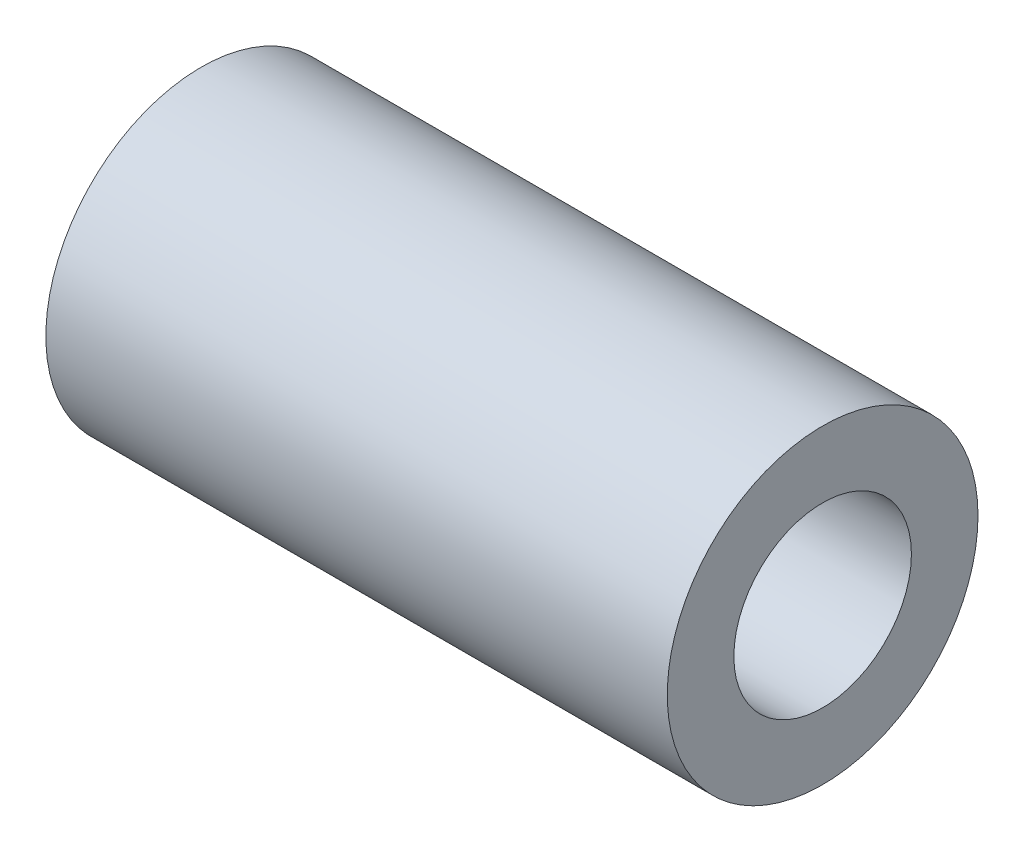
SolidWorks part; units mm, degrees
material "Brass"
ref_plane "Front Plane" through (0, 0, 0) normal (0, 0, 1) x (1, 0, 0)
ref_plane "Top Plane" through (0, 0, 0) normal (0, 1, 0) x (1, 0, 0)
ref_plane "Right Plane" through (0, 0, 0) normal (1, 0, 0) x (0, 0, -1)
sketch "Sketch1" plane through (0, 0, 0) normal (1, 0, 0) x (0, 0, -1)
  circle A0 centre (0, 0) radius 7
  circle A1 centre (0, 0) radius 4
  dimension "D1" = 8
  dimension "D2" = 14
extrude "Boss-Extrude1" add sketch "Sketch1" along normal mid plane 28
